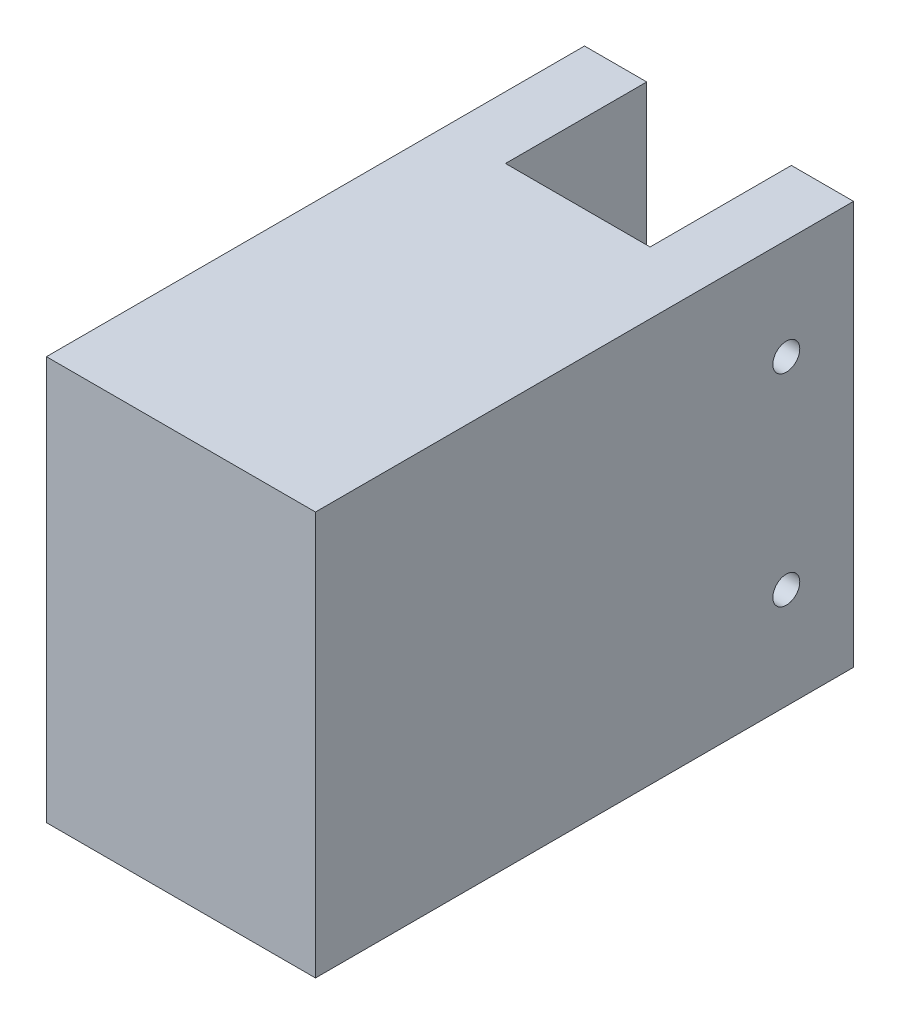
SolidWorks part; units mm, degrees
material "1060 Alloy"
ref_plane "Front Plane" through (0, 0, 0) normal (0, 0, 1) x (1, 0, 0)
ref_plane "Top Plane" through (0, 0, 0) normal (0, 1, 0) x (1, 0, 0)
ref_plane "Right Plane" through (0, 0, 0) normal (1, 0, 0) x (0, 0, -1)
sketch "Sketch1" plane through (0, 0, 0) normal (1, 0, 0) x (0, 0, -1)
  line L1 (30, -30) -> (-30, -30)
  line L2 (30, -30) -> (30, 30)
  line L3 (30, 30) -> (-30, 30)
  line L4 (-30, -30) -> (-30, 30)
  line L5 (30, -30) -> (-30, 30) construction
  line L6 (30, 30) -> (-30, -30) construction
  circle A0 centre (0, 0) radius 17.5
  point P0 (0, 0)
  dimension "D3" = 35
  dimension "D1" = 60
  dimension "D2" = 60
extrude "Boss-Extrude1" add sketch "Sketch1" along normal blind 40
sketch "Sketch2" plane through (0, 0, 30) normal (0, 0, 1) x (1, 0, 0)
  line L0 (40, 30) -> (0, 30) construction
  line L1 (10, 30) -> (30, 30)
  line L2 (10, 30) -> (10, 10)
  line L3 (10, 10) -> (30, 10)
  line L4 (30, 30) -> (30, 10)
  point P8 (20, 30)
  point P9 (20, 10)
  dimension "D1" = 20
  dimension "D2" = 20
sketch "Sketch3" plane through (0, 0, 0) normal (-1, 0, 0) x (0, 0, 1)
  line L4 (30, -30) -> (30, 30)
  line L5 (30, 30) -> (-30, 30)
  line L6 (-30, 30) -> (-30, -30)
  line L7 (-30, -30) -> (30, -30)
  line L8 (30, -30) -> (30, 30)
  line L9 (30, 30) -> (-30, 30)
  line L10 (-30, 30) -> (-30, -30)
  line L11 (-30, -30) -> (30, -30)
  dimension "D1" = 0
sketch "Sketch4" plane through (0, 0, -30) normal (0, 0, -1) x (-1, 0, 0)
  line L0 (-40, -30) -> (0, -30) construction
  line L1 (-40, 30) -> (-30, 30)
  line L2 (-40, 30) -> (-40, -30)
  line L3 (-40, -30) -> (-30, -30)
  line L4 (-30, 30) -> (-30, -30)
  dimension "D1" = 10
extrude "Boss-Extrude2" add sketch "Sketch4" along normal blind 20
sketch "Sketch5" plane through (40, 0, 0) normal (1, 0, 0) x (0, 0, -1)
  line L0 (0, 0) -> (75.5844, 0) construction
  line L1 (-30, -30) -> (50, -30) construction
  line L2 (50, 30) -> (50, -30) construction
  circle A0 centre (40, -15) radius 2
  circle A1 centre (40, 15) radius 2
  dimension "D1" = 4
  dimension "D2" = 15
  dimension "D3" = 10
extrude "Cut-Extrude1" cut sketch "Sketch5" against normal through all
ref_plane "Plane1" through (20, 0, 0) normal (1, 0, 0) x (0, 0, -1)
mirror "Mirror1" about plane through (20, 0, 0) normal (1, 0, 0) of "Cut-Extrude1", "Boss-Extrude2"
sketch "Sketch6" plane through (40, 0, 0) normal (1, 0, 0) x (0, 0, -1)
  circle A0 centre (0, 0) radius 17.5 construction
  circle A1 centre (0, 0) radius 17.5
extrude "Boss-Extrude3" add sketch "Sketch6" against normal blind 15
sketch "Sketch7" plane through (0, 30, 0) normal (0, 1, 0) x (1, 0, 0)
  line L0 (10, 50) -> (0, 50) construction
  line L1 (9.25, 50) -> (30.75, 50)
  line L2 (9.25, 50) -> (9.25, 29)
  line L3 (9.25, 29) -> (30.75, 29)
  line L4 (30.75, 50) -> (30.75, 29)
  line L5 (20, -33) -> (20, 33) construction
  point P6 (20, 29)
  dimension "D1" = 21.5
  dimension "D2" = 21
extrude "Cut-Extrude2" cut sketch "Sketch7" against normal through all
